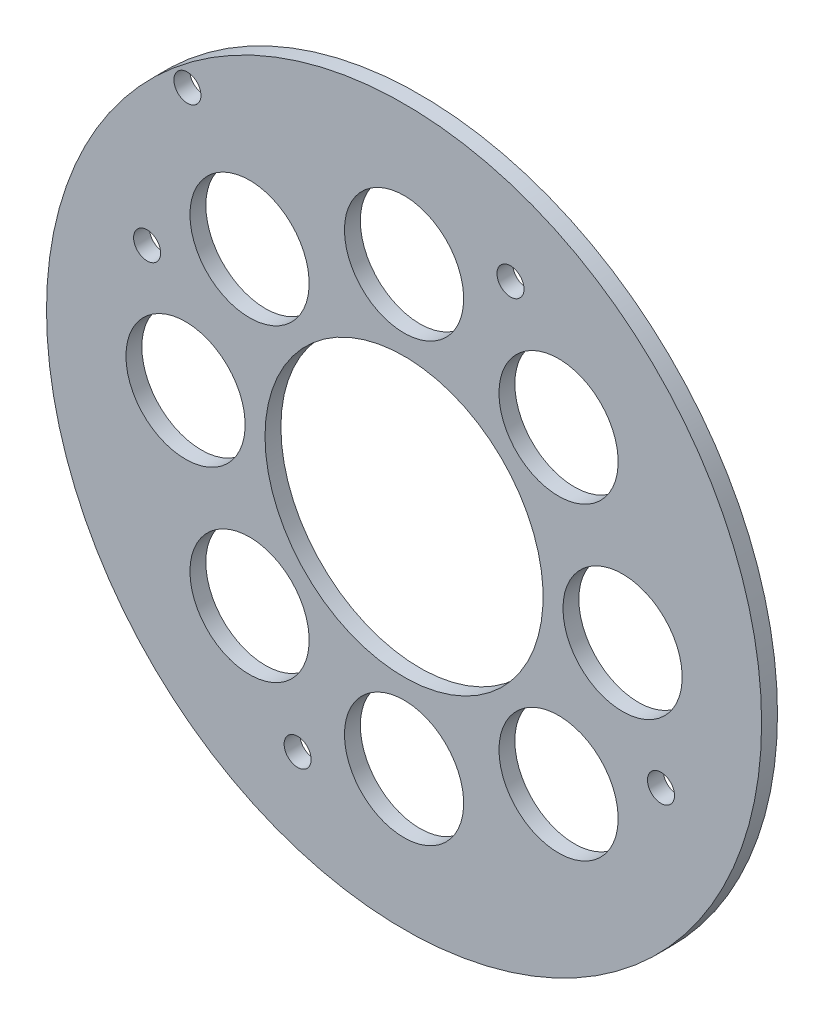
SolidWorks part; units mm, degrees
material "Сплав 2024"
ref_plane "Спереди" through (0, 0, 0) normal (0, 0, 1) x (1, 0, 0)
ref_plane "Сверху" through (0, 0, 0) normal (0, 1, 0) x (1, 0, 0)
ref_plane "Справа" through (0, 0, 0) normal (1, 0, 0) x (0, 0, -1)
sketch "Эскиз1" plane through (0, 0, 0) normal (0, 0, 1) x (1, 0, 0)
  circle A0 centre (0, 0) radius 40
  dimension "D1" = 80
extrude "Бобышка-Вытянуть1" add sketch "Эскиз1" along normal blind 12
sketch "Эскиз8" plane through (0, 0, 12) normal (0, 0, 1) x (1, 0, 0)
  circle A0 centre (0, 0) radius 45
  dimension "D1" = 90
extrude "Бобышка-Вытянуть3" add sketch "Эскиз8" along normal blind 2
sketch "Эскиз2" plane through (0, 0, 14) normal (0, 0, -1) x (-1, 0, 0)
  circle A0 centre (0, 0) radius 7.5
  dimension "D1" = 15
extrude "Вырез-Вытянуть1" cut sketch "Эскиз2" along normal through all
hole_wizard "Отверстие с зазором M31" positions "Эскиз4" profile "Эскиз3" hole size "M3" standard "Ansi Metric" end condition through all
sketch "Эскиз4" plane through (-6.6635, -3.8899, 14) normal (0, 0, -1) x (-1, 0, 0)
  point P0 (20.5996, 37.0106)
sketch "Эскиз3" plane through (-27.2631, 33.1208, 14) normal (1, 0, 0) x (0, -1, 0)
  line L0 (0, 0) -> (0, 14)
  line L1 (0, 14) -> (1.7, 14)
  line L2 (1.7, 14) -> (1.7, 0)
  line L5 (1.7, 0) -> (0, 0)
  line L11 (0, -6.35) -> (0, 107.95) construction
  dimension "Диаметр сквозного отверстия" = 3.4
  dimension "Глубина сквозного отверстия" = 14
sketch "Эскиз10" plane through (0, 0, 0) normal (0, 0, -1) x (-1, 0, 0)
  line L0 (0, 40) -> (0, -40) construction
  line L1 (40, 0) -> (-40, 0) construction
  line L2 (28.3595, 28.2088) -> (-28.3595, -28.2088) construction
  line L3 (-28.3595, 28.2088) -> (28.3595, -28.2088) construction
  circle A0 centre (0, 0) radius 40 construction
  circle A1 centre (0, 0) radius 40 construction
  circle A2 centre (0, 0) radius 27.5 construction
  circle A3 centre (0, 27.5) radius 7.5
  circle A4 centre (19.4454, 19.4454) radius 7.5
  circle A5 centre (27.5, 0) radius 7.5
  circle A6 centre (19.4454, -19.4454) radius 7.5
  circle A7 centre (0, -27.5) radius 7.5
  circle A8 centre (-19.4454, -19.4454) radius 7.5
  circle A9 centre (-27.5, 0) radius 7.5
  circle A10 centre (-19.4454, 19.4454) radius 7.5
  point P34 (0, 0)
  dimension "D1" = 55
  dimension "D2" = 15
  dimension "D3" = 8
sketch "Эскиз11" plane through (0, 0, 14) normal (0, 0, 1) x (1, 0, 0)
  line L0 (0, 40) -> (0, -40) construction
  line L1 (0, 12.5) -> (0, -12.5) construction
  line L2 (12.5, 0) -> (-12.5, 0) construction
  circle A0 centre (0, 0) radius 12.5 construction
  dimension "D1" = 25
hole_wizard "Отверстие с зазором M32" positions "Эскиз13" profile "Эскиз12" hole size "M3" standard "Ansi Metric" end condition through all
sketch "Эскиз13" plane through (0, 0, 14) normal (0, 0, 1) x (1, 0, 0)
  point P0 (0, 12.5)
  point P3 (-12.5, 0)
  point P6 (0, -12.5)
  point P9 (12.5, 0)
sketch "Эскиз12" plane through (0, 12.5, 14) normal (1, 0, 0) x (0, -1, 0)
  line L0 (0, 0) -> (0, 14)
  line L1 (0, 14) -> (1.7, 14)
  line L2 (1.7, 14) -> (1.7, 0)
  line L5 (1.7, 0) -> (0, 0)
  line L11 (0, -6.35) -> (0, 107.95) construction
  dimension "Диаметр сквозного отверстия" = 3.4
  dimension "Глубина сквозного отверстия" = 14
extrude "Вырез-Вытянуть2" cut sketch "Эскиз10" against normal through all
sketch "Эскиз14" plane through (0, 0, 0) normal (0, 0, -1) x (-1, 0, 0)
  line L0 (15.3073, 36.9552) -> (-15.3073, -36.9552) construction
  line L1 (-36.9552, 15.3073) -> (36.9552, -15.3073) construction
  line L2 (-55.8661, 0) -> (55.9948, 0) construction
  line L3 (-15.3073, 36.9552) -> (15.3073, -36.9552) construction
  line L4 (36.9552, 15.3073) -> (-36.9552, -15.3073) construction
  circle A0 centre (0, 0) radius 40 construction
  circle A1 centre (0, 0) radius 40 construction
  circle A2 centre (0, 0) radius 35 construction
  dimension "D3" = 70
  dimension "D1" = 22.5
  dimension "D2" = 22.5
hole_wizard "Отверстие с зазором M33" positions "Эскиз16" profile "Эскиз15" hole size "M3" standard "Ansi Metric" end condition through all
sketch "Эскиз16" plane through (0, 0, 0) normal (0, 0, -1) x (-1, 0, 0)
  line L0 (-15.3073, 36.9552) -> (15.3073, -36.9552) construction
  line L1 (36.9552, 15.3073) -> (-36.9552, -15.3073) construction
  circle A0 centre (0, 0) radius 35 construction
  point P0 (-13.3939, 32.3358)
  point P6 (13.3939, -32.3358)
  point P8 (32.3358, 13.3939)
  point P12 (-32.3358, -13.3939)
sketch "Эскиз15" plane through (13.3939, 32.3358, 0) normal (1, 0, 0) x (0, 1, 0)
  line L0 (0, 0) -> (0, 14)
  line L1 (0, 14) -> (1.7, 14)
  line L2 (1.7, 14) -> (1.7, 0)
  line L5 (1.7, 0) -> (0, 0)
  line L11 (0, -6.35) -> (0, 107.95) construction
  dimension "Диаметр сквозного отверстия" = 3.4
  dimension "Глубина сквозного отверстия" = 14
sketch "Эскиз17" plane through (0, 0, 0) normal (0, 0, -1) x (-1, 0, 0)
  circle A0 centre (0, 0) radius 17
  dimension "D1" = 34
extrude "Вырез-Вытянуть3" cut sketch "Эскиз17" against normal blind 1.5
sketch "Эскиз18" plane through (0, 0, 0) normal (0, 0, -1) x (-1, 0, 0)
  circle A0 centre (0, 0) radius 44.1638
extrude "Вырез-Вытянуть4" cut sketch "Эскиз18" against normal up to surface (12 mm away) up to face at (-25.5631, 33.1208, 12)
sketch "Эскиз19" plane through (0, 0, 12) normal (0, 0, -1) x (-1, 0, 0)
  circle A0 centre (0, 0) radius 17.5
  dimension "D1" = 35
extrude "Вырез-Вытянуть5" cut sketch "Эскиз19" against normal through all
equation "\"D2@Эскиз14\"=\"D1@Эскиз14\""
